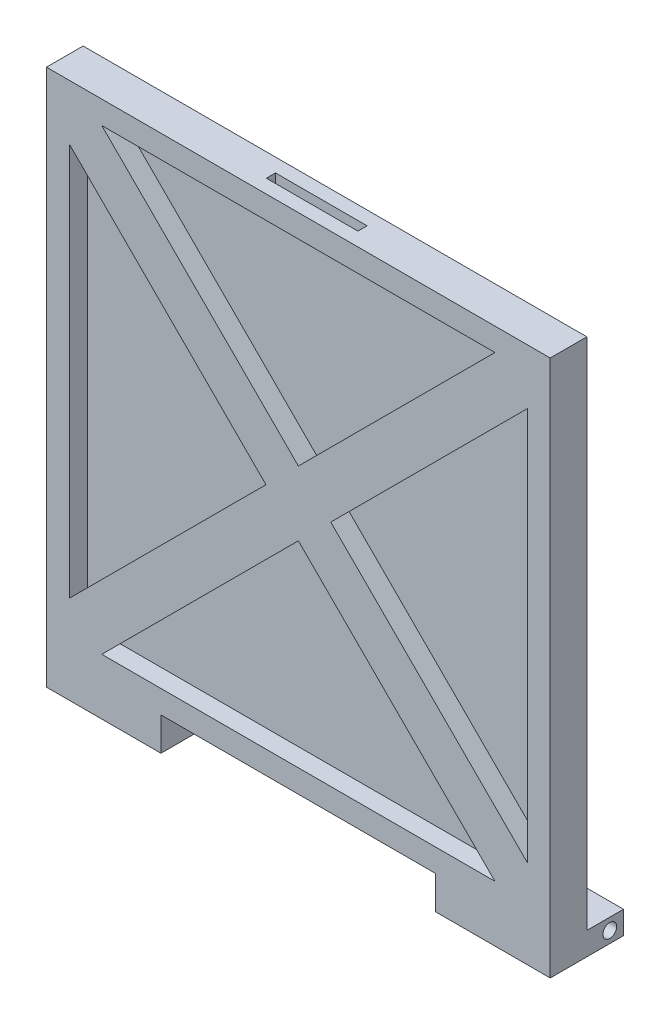
SolidWorks part; units mm, degrees
ref_plane "Front Plane" through (0, 0, 0) normal (0, 0, 1) x (1, 0, 0)
ref_plane "Top Plane" through (0, 0, 0) normal (0, 1, 0) x (1, 0, 0)
ref_plane "Right Plane" through (0, 0, 0) normal (1, 0, 0) x (0, 0, -1)
sketch "Sketch2" plane through (0, 0, 0) normal (0, 0, 1) x (1, 0, 0)
  line L1 (55, -55) -> (-55, -55)
  line L2 (55, -55) -> (55, 55)
  line L3 (55, 55) -> (-55, 55)
  line L4 (-55, -55) -> (-55, 55)
  line L5 (55, -55) -> (-55, 55) construction
  line L6 (55, 55) -> (-55, -55) construction
  point P0 (0, 0)
  dimension "D1" = 110
  dimension "D2" = 110
extrude "Boss-Extrude1" add sketch "Sketch2" along normal blind 8
sketch "Sketch8" plane through (55, 0, 0) normal (1, 0, 0) x (0, 0, -1)
  line L0 (-8, -55) -> (-8, -62.25)
  line L1 (-8, -62.25) -> (8, -62.25)
  line L2 (8, -62.25) -> (8, -57.25)
  line L3 (8, -57.25) -> (0, -57.25)
  line L4 (0, -57.25) -> (0, -55)
  line L5 (0, -55) -> (-8, -55)
  dimension "D1" = 7.25
  dimension "D2" = 16
  dimension "D3" = 5
extrude "Boss-Extrude2" add sketch "Sketch8" against normal blind 25
mirror "Mirror1" about plane through (0, 0, 0) normal (1, 0, 0) of "Boss-Extrude2"
sketch "Sketch10" plane through (-55, 0, 0) normal (-1, 0, 0) x (0, 0, 1)
  line L0 (-5, -59.7629) -> (0, -54.7629) construction
  line L1 (0, 55) -> (0, -57.25) construction
  line L2 (0, -54.7629) -> (-5, -54.7629) construction
  line L3 (-5, -54.7629) -> (-5, -59.7629) construction
  circle A0 centre (-5, -59.7629) radius 1.5
  dimension "D3" = 3
  dimension "D1" = 5
  dimension "D2" = 5
extrude "Cut-Extrude1" cut sketch "Sketch10" against normal through all and the other way through all contours A0
sketch "Sketch11" plane through (0, 0, 8) normal (0, 0, 1) x (1, 0, 0)
  line L0 (-55, 55) -> (0, 0) construction
  line L1 (0, 0) -> (55, 55) construction
  line L2 (0, 0) -> (-55, -55) construction
  line L3 (-55, 55) -> (-55, -62.25) construction
  line L4 (0, 0) -> (55, -55) construction
  line L5 (55, -62.25) -> (55, 55) construction
  line L12 (-42.9289, 50) -> (0, 7.0711)
  line L13 (0, 7.0711) -> (42.9289, 50)
  line L14 (42.9289, 50) -> (-42.9289, 50)
  line L18 (55, 55) -> (-55, 55) construction
  line L19 (50, -42.9289) -> (50, 42.9289)
  line L20 (50, 42.9289) -> (7.0711, 0)
  line L21 (7.0711, 0) -> (50, -42.9289)
  line L22 (-42.9289, -50) -> (42.9289, -50)
  line L23 (42.9289, -50) -> (0, -7.0711)
  line L24 (0, -7.0711) -> (-42.9289, -50)
  line L25 (-50, 42.9289) -> (-50, -42.9289)
  line L26 (-50, -42.9289) -> (-7.0711, 0)
  line L27 (-7.0711, 0) -> (-50, 42.9289)
  point P29 (0, 0)
  dimension "D1" = 5
  dimension "D2" = 5
  dimension "D3" = 5
  dimension "D4" = 4
extrude "Cut-Extrude2" cut sketch "Sketch11" against normal blind 4
sketch "Sketch12" plane through (0, 55, 0) normal (0, 1, 0) x (1, 0, 0)
  line L0 (-10, -3) -> (0, 0) construction
  line L1 (-10, -3) -> (10, -3)
  line L2 (-10, -3) -> (-10, -5)
  line L3 (-10, -5) -> (10, -5)
  line L4 (10, -3) -> (10, -5)
  line L5 (55, 0) -> (-55, 0) construction
  line L6 (0, 0) -> (10, -3) construction
  line L7 (-10, -4) -> (-55, -4) construction
  line L8 (-55, -8) -> (-55, 0) construction
  dimension "D1" = 2
  dimension "D2" = 20
extrude "Cut-Extrude3" cut sketch "Sketch12" against normal blind 2
